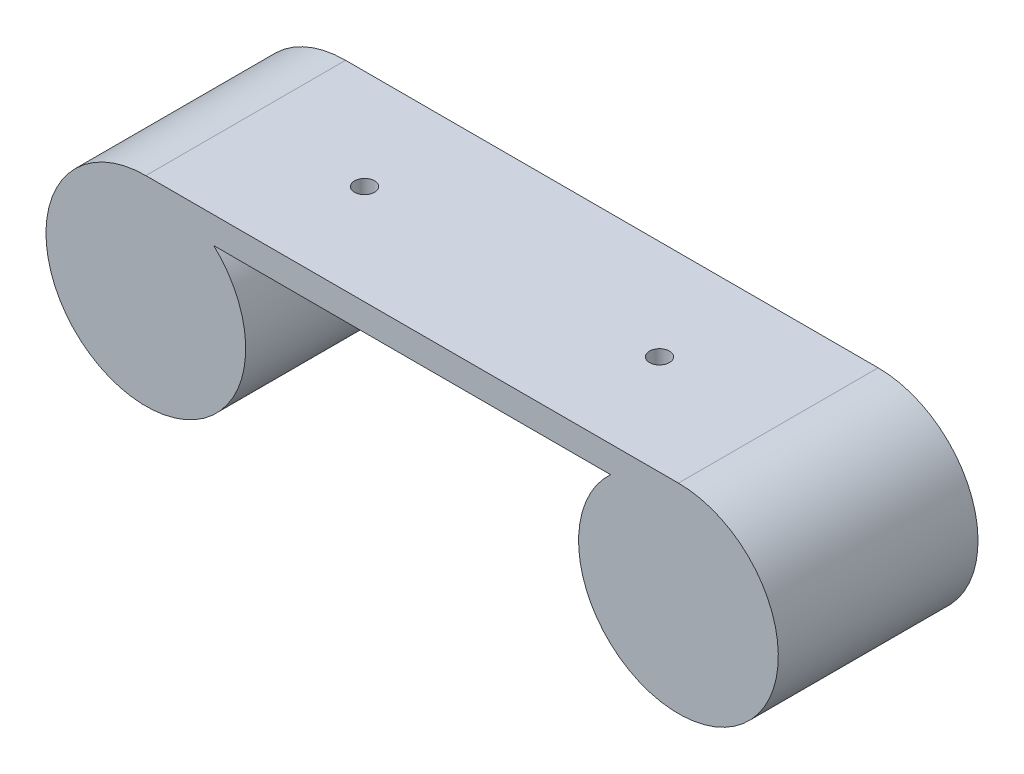
SolidWorks part; units mm, degrees
ref_plane "Front Plane" through (0, 0, 0) normal (0, 0, 1) x (1, 0, 0)
ref_plane "Top Plane" through (0, 0, 0) normal (0, 1, 0) x (1, 0, 0)
ref_plane "Right Plane" through (0, 0, 0) normal (1, 0, 0) x (0, 0, -1)
sketch "Sketch1" plane through (0, 0, 0) normal (0, 0, 1) x (1, 0, 0)
  line L0 (-40, 0) -> (40, 0)
  line L6 (-40, 15) -> (40, 15)
  line L9 (-29.8023, 11.0003) -> (29.8023, 11.0003)
  circle A1 centre (-40, 0) radius 5
  circle A3 centre (40, 0) radius 5
  arc A6 (-40, 15) -> (-29.8023, 11.0003) centre (-40, 0) ccw
  arc A7 (29.8023, 11.0003) -> (40, 15) centre (40, 0) ccw
  point P4 (0, 0)
  dimension "D1" = 10
  dimension "D2" = 30
  dimension "D3" = 30
  dimension "D4" = 10
  dimension "D5" = 80
extrude "Boss-Extrude1" add sketch "Sketch1" along normal blind 30
sketch "Sketch2" plane through (0, 0, 30) normal (0, 0, 1) x (1, 0, 0)
  line L2 (0, 11) -> (9.563, 11)
  line L4 (-29.8023, 11.0003) -> (29.8023, 11.0003) construction
  line L5 (-11.8022, 11.0003) -> (11.8022, 11.0003)
  arc A0 (-8.0467, 7.5) -> (8.0467, 7.5) centre (0, 0) ccw
  circle A1 centre (0, 0) radius 4
  circle A2 centre (7.5, 0) radius 1.75
  circle A3 centre (0, -7.5) radius 1.75
  circle A4 centre (-7.5, 0) radius 1.75
  circle A5 centre (0, 7.5) radius 1.75
  arc A6 (-8.0467, 7.5) -> (-11.8022, 11.0003) centre (-12.85, 6.1114) ccw
  arc A7 (8.0467, 7.5) -> (11.8022, 11.0003) centre (12.85, 6.1114) cw
  point P5 (0, 0)
  dimension "D1" = 22
  dimension "D2" = 8
  dimension "D3" = 3.5
  dimension "D4" = 3.5
  dimension "D5" = 3.5
  dimension "D6" = 3.5
  dimension "D7" = 5
  dimension "D8" = 5
sketch "Sketch3" plane through (0, 15, 0) normal (0, 1, 0) x (1, 0, 0)
  line L0 (0, 0) -> (0, -30) construction
  line L1 (0, -15) -> (22.15, -15) construction
  line L2 (0, -15) -> (-22.15, -15) construction
  line L3 (-40, -30) -> (40, -30) construction
  circle A0 centre (-22.15, -15) radius 1.5
  circle A1 centre (22.15, -15) radius 1.5
  point P7 (0, -15.3372)
  dimension "D3" = 3
  dimension "D1" = 22.15
  dimension "D2" = 22.15
extrude "Cut-Extrude1" cut sketch "Sketch3" against normal blind 6
sketch "Sketch5" plane through (0, 0, 30) normal (0, 0, 1) x (1, 0, 0)
  circle A0 centre (-40, 0) radius 9.45
  circle A1 centre (40, 0) radius 9.45
extrude "Boss-Extrude2" add sketch "Sketch5" against normal blind 2
